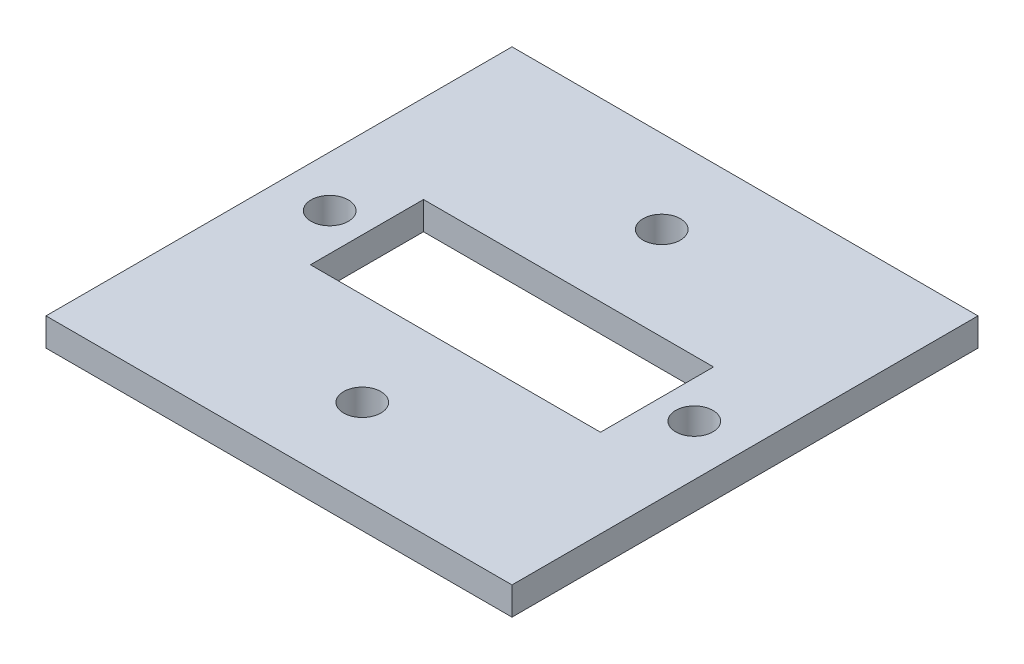
SolidWorks part; units mm, degrees
ref_plane "Plano frontal" through (0, 0, 0) normal (0, 0, 1) x (1, 0, 0)
ref_plane "Plano superior" through (0, 0, 0) normal (0, 1, 0) x (1, 0, 0)
ref_plane "Plano direito" through (0, 0, 0) normal (1, 0, 0) x (0, 0, -1)
sketch "Esboço1" plane through (0, 0, 0) normal (0, 1, 0) x (1, 0, 0)
  line L1 (0, 0) -> (50, 0)
  line L2 (0, 0) -> (0, 50)
  line L3 (0, 50) -> (50, 50)
  line L4 (50, 0) -> (50, 50)
  dimension "D1" = 50
  dimension "D2" = 50
extrude "Base" add sketch "Esboço1" along normal blind 3
sketch "posicaoSensor" plane through (0, 3, 0) normal (0, 1, 0) x (1, 0, 0)
  line L0 (9.44, 37.065) -> (9.44, 12.935) construction
  line L1 (9.44, 12.935) -> (40.56, 12.935) construction
  line L2 (40.56, 12.935) -> (40.56, 37.065) construction
  line L3 (40.56, 37.065) -> (9.44, 37.065) construction
  line L4 (50, 50) -> (0, 50) construction
  line L5 (50, 0) -> (50, 50) construction
  point P4 (25, 37.065)
  point P7 (25, 50)
  point P10 (50, 25)
  point P11 (40.56, 25)
  dimension "D1" = 24.13
  dimension "D2" = 31.12
sketch "EntradasEsb" plane through (0, 3, 0) normal (0, 1, 0) x (1, 0, 0)
  line L1 (9.44, 18.935) -> (40.56, 18.935)
  line L6 (9.44, 31.065) -> (40.56, 31.065)
  line L8 (40.56, 12.935) -> (40.56, 37.065) construction
  line L9 (9.44, 31.065) -> (9.44, 18.935)
  line L10 (40.56, 18.935) -> (40.56, 31.065)
  line L14 (40.56, 37.065) -> (9.44, 37.065) construction
  line L15 (9.44, 12.935) -> (40.56, 12.935) construction
  circle A4 centre (25, 41.065) radius 2
  circle A5 centre (25, 8.935) radius 2
  circle A6 centre (44.56, 25) radius 2
  circle A7 centre (5.44, 25) radius 2
  point P16 (25, 37.065)
  point P20 (25, 12.935)
  point P21 (40.56, 25)
  point P22 (9.44, 25)
  dimension "D4" = 4
  dimension "D7" = 4
  dimension "D5" = 4
  dimension "D6" = 4
  dimension "D1" = 12.13
  dimension "D2" = 31.12
  dimension "D3" = 6
  dimension "D8" = 4
  dimension "D9" = 4
  dimension "D10" = 4
  dimension "D11" = 4
extrude "Corte-extrusão1" cut sketch "EntradasEsb" against normal blind 3
